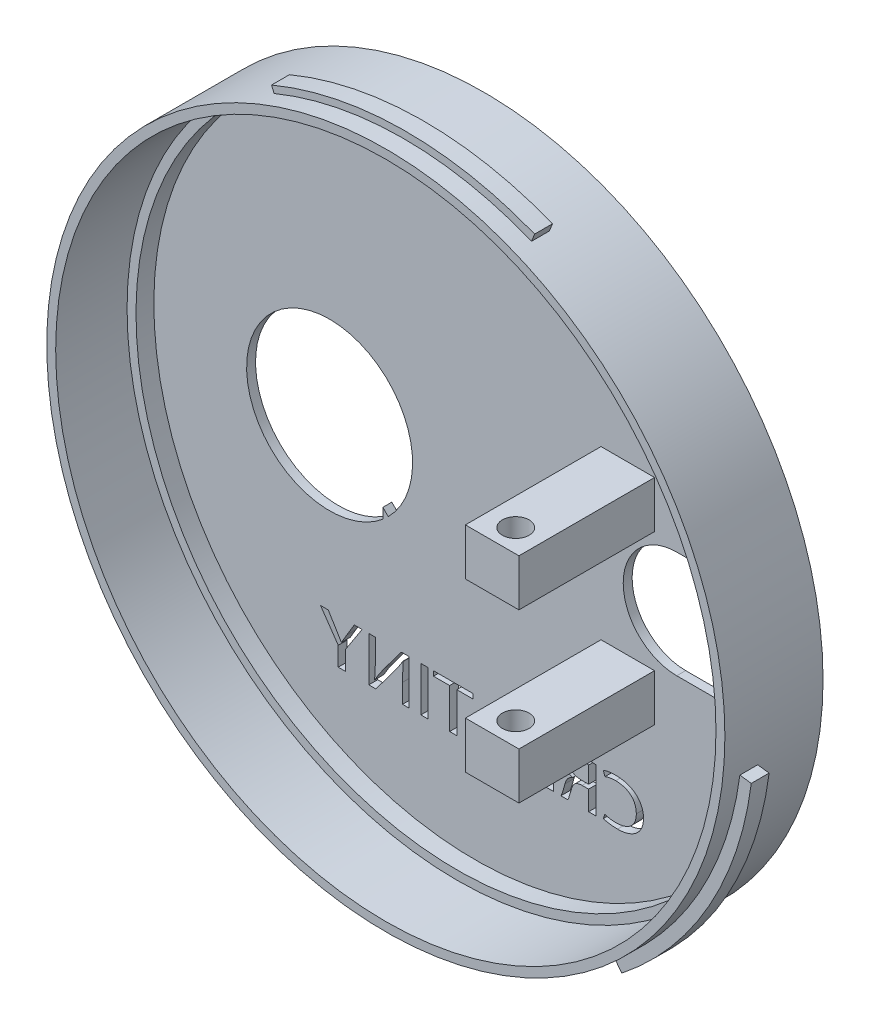
SolidWorks part; units mm, degrees
ref_plane "Front Plane" through (0, 0, 0) normal (0, 0, 1) x (1, 0, 0)
ref_plane "Top Plane" through (0, 0, 0) normal (0, 1, 0) x (1, 0, 0)
ref_plane "Right Plane" through (0, 0, 0) normal (1, 0, 0) x (0, 0, -1)
sketch "Sketch2" plane through (0, 0, 0) normal (0, 0, 1) x (1, 0, 0)
  line L0 (45.3201, -59.6795) -> (45.3201, -57.6795)
  line L1 (35.1466, -44.8333) -> (60.2466, -44.8333)
  line L2 (35.1466, -44.8333) -> (35.1466, -62.4333)
  line L7 (3.2122, -44.4333) -> (-3.6178, -44.4333)
  line L8 (-3.6178, -56.4333) -> (3.2122, -56.4333)
  line L9 (45.3201, -57.6795) -> (61.5355, -57.6795)
  line L10 (45.3201, -61.0295) -> (45.3201, -63.0295)
  line L11 (45.3201, -63.0295) -> (60.9987, -63.0295)
  line L12 (5.7739, -59.6795) -> (5.7739, -57.6795)
  line L13 (5.7739, -57.6795) -> (-10.4415, -57.6795)
  line L14 (5.7739, -61.0295) -> (5.7739, -63.0295)
  line L15 (5.7739, -63.0295) -> (-9.9047, -63.0295)
  line L16 (60.2466, -44.8333) -> (60.2466, -57.6795)
  line L17 (61.0988, -62.4333) -> (63.0314, -62.4333)
  line L20 (35.1466, -62.4333) -> (35.1466, -44.8333)
  line L21 (35.1466, -44.8333) -> (60.2466, -44.8333)
  line L34 (11.6987, -62.4333) -> (35.1466, -62.4333)
  line L35 (11.6987, -60.2582) -> (11.6987, -62.4333)
  line L40 (5.6987, -40.6084) -> (5.6987, -38.4333)
  line L41 (5.6987, -40.6084) -> (11.6987, -40.6084)
  line L42 (5.6987, -38.4333) -> (11.6987, -38.4333)
  line L43 (11.6987, -38.4333) -> (11.6987, -40.6084)
  line L50 (-4.953, -61.0295) -> (5.7739, -61.0295)
  line L51 (-4.953, -59.6795) -> (-4.953, -61.0295)
  line L52 (-4.953, -59.6795) -> (5.7739, -59.6795)
  line L53 (56.047, -59.6795) -> (56.047, -61.0295)
  line L54 (56.047, -59.6795) -> (45.3201, -59.6795)
  line L55 (56.047, -61.0295) -> (45.3201, -61.0295)
  arc A0 (59.5103, -44.8333) -> (60.2466, -47.1822) centre (25.547, -56.7705) ccw
  circle A1 centre (25.547, -56.7705) radius 38
  arc A6 (-3.6178, -44.4333) -> (-3.6178, -56.4333) centre (-3.6178, -50.4333) ccw
  arc A7 (3.2122, -56.4333) -> (3.2122, -44.4333) centre (3.2122, -50.4333) ccw
  circle A16 centre (25.547, -56.7705) radius 38
extrude "Boss-Extrude1" add sketch "Sketch2" along normal blind 10
sketch "Sketch3" plane through (0, 0, 0) normal (0, 0, 1) x (1, 0, 0)
  circle A1 centre (25.547, -56.7705) radius 38
  circle A16 centre (25.547, -56.7705) radius 38
extrude "Boss-Extrude2" add sketch "Sketch3" against normal blind 1 contours A1
sketch "Sketch5" plane through (0, 0, -1) normal (0, 0, -1) x (-1, 0, 0)
  line L0 (-16.2161, -45.0058) -> (8.8839, -45.0058)
  line L1 (-16.2161, -45.0058) -> (-16.2161, -69.0058)
  line L2 (-48.1505, -44.6058) -> (-54.9805, -44.6058)
  line L3 (-54.9805, -56.6058) -> (-48.1505, -56.6058)
  line L4 (8.8839, -45.0058) -> (8.8839, -62.6058)
  line L5 (-16.2161, -69.0058) -> (-16.2161, -45.0058)
  line L6 (-16.2161, -45.0058) -> (8.8839, -45.0058)
  line L7 (-45.664, -60.4307) -> (-39.664, -60.4307)
  line L8 (-45.664, -62.6058) -> (-45.664, -60.4307)
  line L9 (-60.8932, -62.6058) -> (-45.664, -62.6058)
  line L11 (-39.664, -62.6058) -> (-16.2161, -62.6058)
  line L12 (-39.664, -60.4307) -> (-39.664, -62.6058)
  line L13 (-45.664, -40.7808) -> (-45.664, -38.6058)
  line L14 (-45.664, -40.7808) -> (-39.664, -40.7808)
  line L15 (-45.664, -38.6058) -> (-39.664, -38.6058)
  line L16 (-39.664, -38.6058) -> (-39.664, -40.7808)
  line L17 (-56.3157, -61.202) -> (-45.5888, -61.202)
  line L18 (-56.3157, -59.852) -> (-56.3157, -61.202)
  line L19 (-56.3157, -59.852) -> (-45.5888, -59.852)
  line L23 (-16.2161, -69.0058) -> (8.8839, -69.0058)
  line L24 (8.8839, -69.0058) -> (8.8839, -62.6058)
  line L25 (8.8839, -62.6058) -> (11.6687, -62.6058)
  circle A0 centre (-25.8157, -56.943) radius 36
  circle A1 centre (-25.8157, -56.943) radius 38
  arc A2 (-54.9805, -44.6058) -> (-54.9805, -56.6058) centre (-54.9805, -50.6058) ccw
  arc A3 (-48.1505, -56.6058) -> (-48.1505, -44.6058) centre (-48.1505, -50.6058) ccw
  circle A6 centre (-25.8157, -56.943) radius 38
sketch "Sketch8" plane through (0, 0, 0) normal (0, 0, 1) x (1, 0, 0)
  line L0 (12.5096, -32.6319) -> (37.7757, -32.6319) construction
  line L1 (-7.7552, -74.7497) -> (26.2448, -40.7497)
  line L2 (12.5096, -25.7186) -> (37.7757, -25.7186)
  line L3 (12.5096, -39.5451) -> (37.7757, -39.5451)
  line L4 (45.664, -40.7808) -> (45.664, -38.6058)
  line L5 (45.664, -38.6058) -> (39.664, -38.6058)
  line L6 (39.664, -38.6058) -> (39.664, -40.7808)
  line L7 (39.664, -40.7808) -> (45.664, -40.7808)
  line L8 (45.664, -40.7808) -> (45.664, -38.6058)
  line L9 (45.664, -38.6058) -> (39.664, -38.6058)
  line L10 (39.664, -38.6058) -> (39.664, -40.7808)
  line L11 (39.664, -40.7808) -> (45.664, -40.7808)
  line L12 (48.1505, -63.6058) -> (54.9805, -63.6058)
  line L13 (54.9805, -51.6058) -> (48.1505, -51.6058)
  line L14 (-7.7552, -40.7497) -> (26.2448, -40.7497)
  line L15 (-7.7552, -40.7497) -> (-7.7552, -74.7497)
  line L16 (45.664, -62.6058) -> (45.664, -60.4307) construction
  line L17 (60.8932, -62.6058) -> (45.664, -62.6058) construction
  line L25 (56.3157, -61.202) -> (45.5888, -61.202) construction
  line L26 (56.3157, -59.852) -> (56.3157, -61.202) construction
  line L27 (56.3157, -59.852) -> (45.5888, -59.852) construction
  line L29 (-7.7552, -74.7497) -> (26.2448, -74.7497)
  line L32 (45.664, -62.6058) -> (45.664, -60.4307)
  line L33 (60.8932, -62.6058) -> (45.664, -62.6058)
  line L37 (15.2161, -49.0058) -> (6.0771, -49.0058)
  line L38 (15.2161, -49.0058) -> (15.2161, -64.8795)
  line L39 (15.2161, -64.8795) -> (15.2161, -49.0058)
  line L40 (15.2161, -49.0058) -> (6.0771, -49.0058)
  line L41 (56.3157, -61.202) -> (45.5888, -61.202)
  line L42 (56.3157, -59.852) -> (56.3157, -61.202)
  line L43 (56.3157, -59.852) -> (45.5888, -59.852)
  line L46 (-9.1476, -49.0058) -> (-9.8839, -49.0058)
  line L47 (26.2448, -40.7497) -> (26.2448, -74.7497)
  line L48 (-7.7552, -40.7497) -> (26.2448, -74.7497)
  circle A0 centre (9.2448, -57.7497) radius 9.3
  arc A1 (12.5096, -25.7186) -> (12.5096, -39.5451) centre (12.5096, -32.6319) ccw
  arc A3 (37.7757, -39.5451) -> (37.7757, -25.7186) centre (37.7757, -32.6319) ccw
  arc A10 (54.9805, -63.6058) -> (54.9805, -51.6058) centre (54.9805, -57.6058) ccw
  arc A11 (48.1505, -51.6058) -> (48.1505, -63.6058) centre (48.1505, -57.6058) ccw
  point P4 (25.1426, -32.6319)
  point P9 (12.5096, -29.4603)
  point P10 (25.1426, -36.3735)
  point P21 (9.2448, -57.7497)
  dimension "D6" = 18.6
  dimension "D7" = 34
  dimension "D4" = 0
extrude "Cut-Extrude3" cut sketch "Sketch8" against normal blind 11
sketch "Sketch9" plane through (0, 0, 0) normal (0, 0, 1) x (1, 0, 0)
  line L0 (-8.8839, -62.6058) -> (-11.6687, -62.6058) construction
  line L8 (45.664, -47.7808) -> (45.664, -45.6058)
  line L9 (45.664, -45.6058) -> (39.664, -45.6058)
  line L10 (39.664, -45.6058) -> (39.664, -47.7808)
  line L12 (48.1505, -63.6058) -> (54.9805, -63.6058)
  line L13 (54.9805, -51.6058) -> (48.1505, -51.6058)
  line L18 (-8.8839, -45.0058) -> (-8.8839, -62.6058) construction
  line L19 (16.2161, -69.0058) -> (-8.8839, -69.0058) construction
  line L20 (-8.8839, -69.0058) -> (-8.8839, -62.6058) construction
  line L21 (16.2161, -45.0058) -> (-8.8839, -45.0058) construction
  line L22 (16.2161, -45.0058) -> (16.2161, -69.0058) construction
  line L23 (16.2161, -69.0058) -> (16.2161, -45.0058) construction
  line L24 (16.2161, -45.0058) -> (-8.8839, -45.0058) construction
  line L28 (-8.8839, -62.6058) -> (-11.6687, -62.6058)
  line L29 (39.664, -69.6058) -> (16.2161, -69.6058)
  line L30 (39.664, -67.4307) -> (39.664, -69.6058)
  line L31 (45.664, -64.3558) -> (45.664, -69.6058)
  line L32 (45.664, -69.6058) -> (39.664, -69.6058)
  line L34 (-8.8839, -45.0058) -> (-8.8839, -62.6058)
  line L35 (16.2161, -69.0058) -> (-8.8839, -69.0058)
  line L36 (-8.8839, -69.0058) -> (-8.8839, -62.6058)
  line L37 (16.2161, -45.0058) -> (-8.8839, -45.0058)
  line L38 (16.2161, -45.0058) -> (16.2161, -69.0058)
  line L39 (16.2161, -69.0058) -> (16.2161, -45.0058)
  line L40 (16.2161, -45.0058) -> (-8.8839, -45.0058)
  line L41 (45.664, -68.202) -> (45.5888, -68.202)
  line L42 (56.3157, -66.852) -> (56.3157, -68.202)
  line L44 (39.664, -47.7808) -> (39.664, -67.4307)
  line L45 (39.664, -47.7808) -> (39.664, -50.8558)
  line L46 (39.664, -50.8558) -> (45.664, -50.8558)
  line L47 (45.664, -50.8558) -> (45.664, -47.7808)
  line L48 (39.664, -57.6058) -> (45.664, -57.6058)
  line L49 (39.664, -64.3558) -> (45.664, -64.3558)
  circle A2 centre (25.8157, -63.943) radius 38
  circle A4 centre (25.8157, -63.943) radius 36
  circle A6 centre (25.8157, -63.943) radius 38
  arc A10 (54.9805, -63.6058) -> (54.9805, -51.6058) centre (54.9805, -57.6058) ccw
  arc A11 (48.1505, -51.6058) -> (48.1505, -63.6058) centre (48.1505, -57.6058) ccw
  dimension "D6" = 13.5
extrude "Boss-Extrude3" add sketch "Sketch9" along normal blind 15.2
sketch "Sketch10" plane through (0, -45.6058, 0) normal (0, 1, 0) x (1, 0, 0)
  circle A0 centre (42.7464, -12.6397) radius 1.5
sketch "Sketch11" plane through (45.3201, 0, 0) normal (1, 0, 0) x (0, 0, -1)
  line L0 (-10, -59.6795) -> (-10, -57.6795) construction
  line L1 (-10, -57.6795) -> (-15.2, -57.6795) construction
  line L2 (-15.2, -57.6795) -> (-15.2, -59.6795) construction
  line L3 (-15.2, -59.6795) -> (-10, -59.6795) construction
  line L4 (-10, -62.6058) -> (-10, -61.0295) construction
  line L5 (-10, -61.0295) -> (-15.2, -61.0295) construction
  line L6 (-15.2, -61.0295) -> (-15.2, -62.6058) construction
  line L7 (-15.2, -62.6058) -> (-10, -62.6058) construction
  line L8 (-10, -59.6795) -> (-10, -57.6795)
  line L9 (-10, -57.6795) -> (-15.2, -57.6795)
  line L10 (-15.2, -57.6795) -> (-15.2, -59.6795)
  line L11 (-15.2, -59.6795) -> (-10, -59.6795)
  line L12 (-10, -62.6058) -> (-10, -61.0295)
  line L13 (-10, -61.0295) -> (-15.2, -61.0295)
  line L14 (-15.2, -61.0295) -> (-15.2, -62.6058)
  line L15 (-15.2, -62.6058) -> (-10, -62.6058)
sketch "Sketch12" plane through (0, -69.6058, 0) normal (0, -1, 0) x (1, 0, 0)
  line L4 (45.664, 0) -> (45.664, 15.2)
  line L6 (39.664, 0) -> (45.664, 0)
  line L7 (39.664, 0) -> (45.664, 0)
  line L8 (45.664, 0) -> (45.664, 15.2)
  line L10 (45.664, 15.2) -> (39.664, 15.2)
  line L11 (39.664, 15.2) -> (39.664, 0)
  line L16 (45.664, 15.2) -> (39.664, 15.2)
  line L17 (39.664, 15.2) -> (39.664, 0)
  dimension "D1" = 0
extrude "Cut-Extrude5" cut sketch "Sketch10" against normal blind 30.2
sketch "Sketch13" plane through (0, 0, -1) normal (0, 0, -1) x (-1, 0, 0)
  line L0 (-40.1042, -77.4203) -> (-39.9192, -76.8935)
  line L1 (-39.9284, -81.5787) -> (-40.0866, -81.0683)
  line L2 (-39.0729, -81.7438) -> (-38.2711, -81.7438)
  line L3 (-38.2711, -81.7438) -> (-38.2711, -79.5483)
  line L4 (-38.2711, -79.5483) -> (-37.5423, -79.5483)
  line L5 (-35.949, -81.7449) -> (-35.1716, -81.7438)
  line L6 (-36.485, -79.3339) -> (-36.4847, -79.3196)
  line L7 (-39.0729, -76.7738) -> (-39.0729, -81.7438)
  line L8 (-37.481, -79.0766) -> (-38.2711, -79.0766)
  line L9 (-38.2711, -79.0766) -> (-38.2711, -77.2076)
  line L10 (-31.2381, -78.8742) -> (-33.5369, -78.8742)
  line L11 (-33.5369, -78.8742) -> (-33.5369, -77.2807)
  line L12 (-33.5369, -77.2807) -> (-31.0972, -77.2807)
  line L13 (-31.0972, -77.2807) -> (-31.0972, -76.7472)
  line L14 (-31.0972, -76.7472) -> (-34.3388, -76.7472)
  line L15 (-34.3388, -76.7472) -> (-34.3388, -81.7404)
  line L16 (-34.3388, -81.7404) -> (-30.9651, -81.7404)
  line L17 (-30.9651, -81.7404) -> (-30.9651, -81.2069)
  line L18 (-30.9651, -81.2069) -> (-33.5369, -81.2069)
  line L19 (-33.5369, -81.2069) -> (-33.5369, -79.4077)
  line L20 (-33.5369, -79.4077) -> (-31.2381, -79.4077)
  line L21 (-31.2381, -79.4077) -> (-31.2381, -78.8742)
  line L22 (-26.9456, -80.1658) -> (-26.3161, -81.7438)
  line L23 (-26.3161, -81.7438) -> (-25.503, -81.7438)
  line L24 (-25.503, -81.7438) -> (-27.514, -76.7472)
  line L25 (-27.514, -76.7472) -> (-28.4234, -76.7472)
  line L26 (-28.4234, -76.7472) -> (-30.4344, -81.7438)
  line L27 (-30.4344, -81.7438) -> (-29.6387, -81.7438)
  line L28 (-29.6387, -81.7438) -> (-29.0354, -80.1658)
  line L29 (-29.0354, -80.1658) -> (-26.9456, -80.1658)
  line L30 (-28.878, -79.6941) -> (-28.3009, -78.2095)
  line L31 (-28.0127, -77.2809) -> (-27.9862, -77.2807)
  line L32 (-27.6804, -78.2179) -> (-27.103, -79.6941)
  line L33 (-27.103, -79.6941) -> (-28.878, -79.6941)
  line L34 (-23.4983, -81.7438) -> (-22.6964, -81.7438)
  line L35 (-22.6964, -81.7438) -> (-22.6964, -77.2807)
  line L36 (-22.6964, -77.2807) -> (-20.8821, -77.2807)
  line L37 (-20.8821, -77.2807) -> (-20.8821, -76.7472)
  line L38 (-20.8821, -76.7472) -> (-25.3039, -76.7472)
  line L39 (-25.3039, -76.7472) -> (-25.3039, -77.2807)
  line L40 (-25.3039, -77.2807) -> (-23.4983, -77.2807)
  line L41 (-23.4983, -77.2807) -> (-23.4983, -81.7438)
  line L42 (-20.2736, -76.7438) -> (-20.2736, -81.7438)
  line L43 (-20.2736, -81.7438) -> (-19.4717, -81.7438)
  line L44 (-19.4717, -81.7438) -> (-19.4717, -76.7438)
  line L45 (-19.4717, -76.7438) -> (-20.2736, -76.7438)
  line L46 (-17.4134, -81.7438) -> (-17.4134, -79.6073)
  line L47 (-17.4756, -77.5607) -> (-17.4487, -77.5522)
  line L48 (-16.3296, -79.216) -> (-14.4266, -81.7438)
  line L49 (-14.4266, -81.7438) -> (-13.6398, -81.7438)
  line L50 (-13.6398, -81.7438) -> (-13.6398, -76.7503)
  line L51 (-13.6398, -76.7503) -> (-14.3731, -76.7503)
  line L52 (-14.3731, -76.7503) -> (-14.3731, -78.8535)
  line L53 (-14.2841, -80.9226) -> (-14.3016, -80.9291)
  line L54 (-15.3787, -79.2856) -> (-17.289, -76.7438)
  line L55 (-17.289, -76.7438) -> (-18.1467, -76.7438)
  line L56 (-18.1467, -76.7438) -> (-18.1467, -81.7438)
  line L57 (-18.1467, -81.7438) -> (-17.4134, -81.7438)
  line L58 (-10.2093, -81.7438) -> (-10.2093, -79.6147)
  line L59 (-10.2093, -79.6147) -> (-8.2276, -76.7438)
  line L60 (-8.2276, -76.7438) -> (-9.0907, -76.7438)
  line L61 (-9.0907, -76.7438) -> (-9.9451, -78.1236)
  line L62 (-10.5556, -79.1549) -> (-10.5738, -79.1548)
  line L63 (-11.1795, -78.1246) -> (-12.0153, -76.7438)
  line L64 (-12.0153, -76.7438) -> (-12.8872, -76.7438)
  line L65 (-12.8872, -76.7438) -> (-11.0112, -79.6296)
  line L66 (-11.0112, -79.6296) -> (-11.0112, -81.7438)
  line L67 (-11.0112, -81.7438) -> (-10.2093, -81.7438)
  spline S0 degree 3 poles (-40.0866, -81.0683) (-40.1716, -81.1015) (-40.3066, -81.1465) (-40.4973, -81.1914) (-40.8255, -81.2531) (-41.1089, -81.2756) (-41.3382, -81.2764) knots 0 0 0 0 0.214735 0.334 0.460607 1 1 1 1
  spline S1 degree 3 poles (-41.3382, -81.2764) (-41.51, -81.2759) (-41.7608, -81.2566) (-42.0826, -81.1991) (-42.3021, -81.1394) (-42.5053, -81.0618) (-42.6937, -80.9697) (-42.8659, -80.8599) (-43.0218, -80.7342) (-43.1607, -80.5941) (-43.2826, -80.4418) (-43.385, -80.2759) (-43.4699, -80.0989) (-43.5359, -79.909) (-43.599, -79.6335) (-43.6196, -79.4177) (-43.6195, -79.2706) knots 0 0 0 0 0.15004 0.219227 0.285263 0.348397 0.408985 0.468216 0.526376 0.583546 0.640195 0.696413 0.753518 0.811369 0.871641 1 1 1 1
  spline S2 degree 3 poles (-43.6195, -79.2706) (-43.6176, -79.1147) (-43.5971, -78.8858) (-43.5275, -78.5948) (-43.4566, -78.3964) (-43.367, -78.2128) (-43.2594, -78.0425) (-43.1306, -77.8879) (-42.9848, -77.7471) (-42.8221, -77.6228) (-42.6454, -77.514) (-42.4546, -77.4217) (-42.2504, -77.3456) (-42.0325, -77.2865) (-41.7164, -77.2307) (-41.4707, -77.2122) (-41.3028, -77.2123) knots 0 0 0 0 0.133608 0.195976 0.255817 0.313729 0.370712 0.427898 0.485703 0.543993 0.602954 0.663194 0.725286 0.789374 0.856265 1 1 1 1
  spline S3 degree 3 poles (-41.3028, -77.2123) (-41.1837, -77.2153) (-41.0094, -77.2218) (-40.7847, -77.2478) (-40.6299, -77.2692) (-40.4848, -77.2988) (-40.3082, -77.342) (-40.1835, -77.3879) (-40.1042, -77.4203) knots 0 0 0 0 0.292162 0.427032 0.554525 0.675142 0.789885 1 1 1 1
  spline S4 degree 3 poles (-39.9192, -76.8935) (-39.9851, -76.8648) (-40.099, -76.8277) (-40.2693, -76.785) (-40.4337, -76.7508) (-40.6227, -76.7192) (-40.9236, -76.6888) (-41.1619, -76.6816) (-41.3285, -76.6795) knots 0 0 0 0 0.150126 0.250436 0.36734 0.501483 0.651141 1 1 1 1
  spline S5 degree 3 poles (-41.3285, -76.6795) (-41.5511, -76.6823) (-41.8781, -76.7051) (-42.2974, -76.7842) (-42.5881, -76.8617) (-42.8602, -76.9638) (-43.1153, -77.0864) (-43.3524, -77.2306) (-43.5707, -77.3954) (-43.7686, -77.5782) (-43.9406, -77.7786) (-44.0882, -77.9934) (-44.2085, -78.224) (-44.3033, -78.4697) (-44.3985, -78.8237) (-44.4244, -79.1031) (-44.4289, -79.2921) knots 0 0 0 0 0.146906 0.215514 0.281217 0.345142 0.406923 0.467645 0.527896 0.587107 0.644942 0.701759 0.758695 0.816084 0.875151 1 1 1 1
  spline S6 degree 3 poles (-44.4289, -79.2921) (-44.426, -79.4864) (-44.3965, -79.7706) (-44.3049, -80.1309) (-44.2124, -80.3759) (-44.0954, -80.6027) (-43.9521, -80.8103) (-43.7854, -81.0003) (-43.5935, -81.1691) (-43.383, -81.3187) (-43.1574, -81.4499) (-42.9172, -81.5607) (-42.6626, -81.6507) (-42.3938, -81.7217) (-42.0078, -81.7891) (-41.7087, -81.8093) (-41.5054, -81.8092) knots 0 0 0 0 0.134055 0.196188 0.256038 0.314374 0.371821 0.429644 0.488327 0.547714 0.607594 0.668158 0.729921 0.793672 0.859787 1 1 1 1
  spline S7 degree 3 poles (-41.5054, -81.8092) (-41.3334, -81.8071) (-41.0844, -81.7995) (-40.7654, -81.7688) (-40.5545, -81.7378) (-40.3647, -81.7016) (-40.1569, -81.6533) (-40.0137, -81.6129) (-39.9284, -81.5787) knots 0 0 0 0 0.322336 0.466303 0.600284 0.721615 0.828154 1 1 1 1
  spline S8 degree 3 poles (-37.5423, -79.5483) (-37.4609, -79.5518) (-37.3421, -79.56) (-37.1896, -79.5863) (-37.0857, -79.6124) (-36.99, -79.6474) (-36.901, -79.6869) (-36.8192, -79.7337) (-36.7455, -79.7896) (-36.6773, -79.8521) (-36.6148, -79.9233) (-36.5583, -80.0038) (-36.5037, -80.0913) (-36.4578, -80.19) (-36.3965, -80.3353) (-36.3629, -80.4526) (-36.3435, -80.5335) knots 0 0 0 0 0.143269 0.208951 0.271875 0.331287 0.387798 0.442963 0.496357 0.55015 0.605343 0.662521 0.722851 0.786347 0.853658 1 1 1 1
  spline S9 degree 3 poles (-36.3435, -80.5335) (-36.3074, -80.6797) (-36.2459, -80.8862) (-36.1729, -81.1499) (-36.1206, -81.3152) (-36.0755, -81.4589) (-36.02, -81.6004) (-35.9818, -81.6948) (-35.949, -81.7449) knots 0 0 0 0 0.353682 0.506518 0.642777 0.761214 0.86009 1 1 1 1
  spline S10 degree 3 poles (-35.1716, -81.7438) (-35.2095, -81.6801) (-35.2581, -81.5666) (-35.3223, -81.3983) (-35.3763, -81.2359) (-35.4342, -81.0501) (-35.5203, -80.7542) (-35.5799, -80.5182) (-35.6231, -80.3534) knots 0 0 0 0 0.151417 0.252399 0.369032 0.501655 0.651028 1 1 1 1
  spline S11 degree 3 poles (-35.6231, -80.3534) (-35.6562, -80.2307) (-35.7155, -80.053) (-35.833, -79.8401) (-35.9299, -79.6993) (-36.0435, -79.5762) (-36.2204, -79.4374) (-36.3762, -79.367) (-36.485, -79.3339) knots 0 0 0 0 0.272814 0.398603 0.520133 0.638269 0.756086 1 1 1 1
  spline S12 degree 3 poles (-36.4847, -79.3196) (-36.4074, -79.2994) (-36.2947, -79.261) (-36.1519, -79.1959) (-36.0505, -79.1424) (-35.9549, -79.0822) (-35.8645, -79.0156) (-35.7801, -78.9424) (-35.7001, -78.8646) (-35.6285, -78.7798) (-35.5648, -78.6897) (-35.5109, -78.5933) (-35.466, -78.4917) (-35.43, -78.3842) (-35.3957, -78.2303) (-35.3851, -78.1104) (-35.383, -78.0292) knots 0 0 0 0 0.130854 0.194485 0.256783 0.31831 0.379398 0.440388 0.50121 0.56182 0.621883 0.681614 0.74239 0.803451 0.867044 1 1 1 1
  spline S13 degree 3 poles (-35.383, -78.0292) (-35.3842, -77.9328) (-35.398, -77.7897) (-35.4488, -77.6073) (-35.5016, -77.4799) (-35.5669, -77.3602) (-35.6721, -77.2144) (-35.7666, -77.118) (-35.8375, -77.0633) knots 0 0 0 0 0.261906 0.387866 0.512745 0.635647 0.757361 1 1 1 1
  spline S14 degree 3 poles (-35.8375, -77.0633) (-35.9322, -76.9931) (-36.0925, -76.9045) (-36.3291, -76.8189) (-36.531, -76.7653) (-36.7549, -76.7256) (-37.0994, -76.6835) (-37.3715, -76.6767) (-37.5603, -76.6763) knots 0 0 0 0 0.196744 0.304308 0.419971 0.545727 0.684174 1 1 1 1
  spline S15 degree 3 poles (-37.5603, -76.6763) (-37.8281, -76.677) (-38.1605, -76.6861) (-38.5528, -76.7138) (-38.7896, -76.7365) (-38.9619, -76.7564) (-39.0729, -76.7738) knots 0 0 0 0 0.529595 0.657124 0.777787 1 1 1 1
  spline S16 degree 3 poles (-38.2711, -77.2076) (-38.232, -77.1968) (-38.1665, -77.1857) (-38.0711, -77.174) (-37.9817, -77.1652) (-37.8802, -77.1594) (-37.7208, -77.1518) (-37.5953, -77.1484) (-37.5078, -77.148) knots 0 0 0 0 0.158138 0.259553 0.376096 0.509139 0.657456 1 1 1 1
  spline S17 degree 3 poles (-37.5078, -77.148) (-37.4091, -77.1491) (-37.2643, -77.1544) (-37.0777, -77.1798) (-36.9489, -77.2038) (-36.8282, -77.2361) (-36.7151, -77.2756) (-36.6099, -77.3231) (-36.5121, -77.3761) (-36.4234, -77.4369) (-36.3465, -77.5071) (-36.2814, -77.5864) (-36.2279, -77.6739) (-36.1837, -77.7691) (-36.1442, -77.9127) (-36.1307, -78.0263) (-36.1291, -78.1043) knots 0 0 0 0 0.15648 0.229013 0.298179 0.363815 0.426835 0.487646 0.546422 0.602954 0.657444 0.710935 0.76482 0.819539 0.87669 1 1 1 1
  spline S18 degree 3 poles (-36.1291, -78.1043) (-36.1304, -78.1753) (-36.1424, -78.2798) (-36.1815, -78.4125) (-36.2231, -78.5037) (-36.2731, -78.5905) (-36.3364, -78.6705) (-36.4109, -78.744) (-36.4944, -78.8135) (-36.5891, -78.8736) (-36.6913, -78.9278) (-36.8023, -78.9729) (-36.9221, -79.0086) (-37.0497, -79.0392) (-37.2365, -79.068) (-37.3818, -79.0752) (-37.481, -79.0766) knots 0 0 0 0 0.114278 0.168309 0.221849 0.275202 0.329267 0.385379 0.443396 0.503687 0.565418 0.629381 0.696136 0.766433 0.840361 1 1 1 1
  spline S19 degree 2 poles (-28.3009, -78.2095) (-28.1338, -77.7524) (-28.0127, -77.2809) knots 0 0 0 1 1 1
  spline S20 degree 3 poles (-27.9862, -77.2807) (-27.9457, -77.4335) (-27.8483, -77.7475) (-27.7406, -78.0581) (-27.6804, -78.2179) knots 0 0 0 0 0.480444 1 1 1 1
  spline S21 degree 3 poles (-17.4134, -79.6073) (-17.4147, -79.4151) (-17.4135, -79.1337) (-17.4218, -78.7685) (-17.4335, -78.2783) (-17.454, -77.8774) (-17.4756, -77.5607) knots 0 0 0 0 0.281665 0.412035 0.53509 1 1 1 1
  spline S22 degree 3 poles (-17.4487, -77.5522) (-17.2905, -77.8359) (-16.9313, -78.4008) (-16.5362, -78.9409) (-16.3296, -79.216) knots 0 0 0 0 0.485601 1 1 1 1
  spline S23 degree 3 poles (-14.3731, -78.8535) (-14.3746, -79.0397) (-14.372, -79.3138) (-14.3653, -79.6723) (-14.3482, -80.1765) (-14.3191, -80.5923) (-14.2841, -80.9226) knots 0 0 0 0 0.269628 0.396926 0.519093 1 1 1 1
  spline S24 degree 3 poles (-14.3016, -80.9291) (-14.3755, -80.7987) (-14.4897, -80.6011) (-14.6539, -80.3394) (-14.7841, -80.1355) (-14.9231, -79.9289) (-15.1186, -79.6428) (-15.2724, -79.4287) (-15.3787, -79.2856) knots 0 0 0 0 0.228666 0.348185 0.471297 0.597869 0.728081 1 1 1 1
  spline S25 degree 3 poles (-9.9451, -78.1236) (-10.0578, -78.3005) (-10.2668, -78.6411) (-10.4666, -78.9871) (-10.5556, -79.1549) knots 0 0 0 0 0.524939 1 1 1 1
  spline S26 degree 3 poles (-10.5738, -79.1548) (-10.6684, -78.9878) (-10.8682, -78.6431) (-11.0733, -78.3016) (-11.1795, -78.1246) knots 0 0 0 0 0.481859 1 1 1 1
extrude "Cut-Extrude6" cut sketch "Sketch13" against normal blind 1
sketch "Sketch14" plane through (0, 0, 0) normal (0, 0, 1) x (1, 0, 0)
  line L0 (10.7422, -20.9737) -> (11.5651, -22.9375)
  line L1 (40.2235, -20.7019) -> (39.4369, -22.6805)
  line L2 (64.5028, -61.8735) -> (62.3906, -61.6043)
  line L3 (49.9975, -87.541) -> (48.6773, -85.8705)
  line L4 (2.2022, -87.9817) -> (3.4914, -86.2871)
  line L5 (-12.7739, -62.586) -> (-10.667, -62.2779)
  arc A0 (40.2235, -20.7019) -> (10.7422, -20.9737) centre (25.8157, -56.943) ccw
  arc A2 (39.4369, -22.6805) -> (11.5651, -22.9375) centre (25.8157, -56.943) ccw
  arc A4 (49.9975, -87.541) -> (64.5028, -61.8735) centre (25.8157, -56.943) ccw
  arc A5 (-12.7739, -62.586) -> (2.2022, -87.9817) centre (25.8157, -56.943) ccw
  arc A6 (48.6773, -85.8705) -> (62.3906, -61.6043) centre (25.8157, -56.943) ccw
  arc A7 (-10.667, -62.2779) -> (3.4914, -86.2871) centre (25.8157, -56.943) ccw
  point P17 (25.8157, -56.943)
  point P23 (25.8157, -56.943)
  dimension "D1" = 3
  dimension "D2" = 3
sketch "Sketch15" plane through (0, 0, 10) normal (0, 0, 1) x (1, 0, 0)
  line L0 (39.8653, -21.5713) -> (40.2235, -20.7019)
  circle A0 centre (25.547, -56.7705) radius 38 construction
  circle A1 centre (25.8157, -56.943) radius 39 construction
  point P6 (40.0444, -21.1366)
extrude "Boss-Extrude5" add sketch "Sketch14" along normal blind 2 from offset 6
sketch "Sketch17" plane through (0, 0, 10) normal (0, 0, 1) x (1, 0, 0)
  circle A0 centre (25.547, -56.7705) radius 37
  circle A1 centre (25.547, -56.7705) radius 34.5561
extrude "Cut-Extrude7" cut sketch "Sketch17" against normal blind 8
